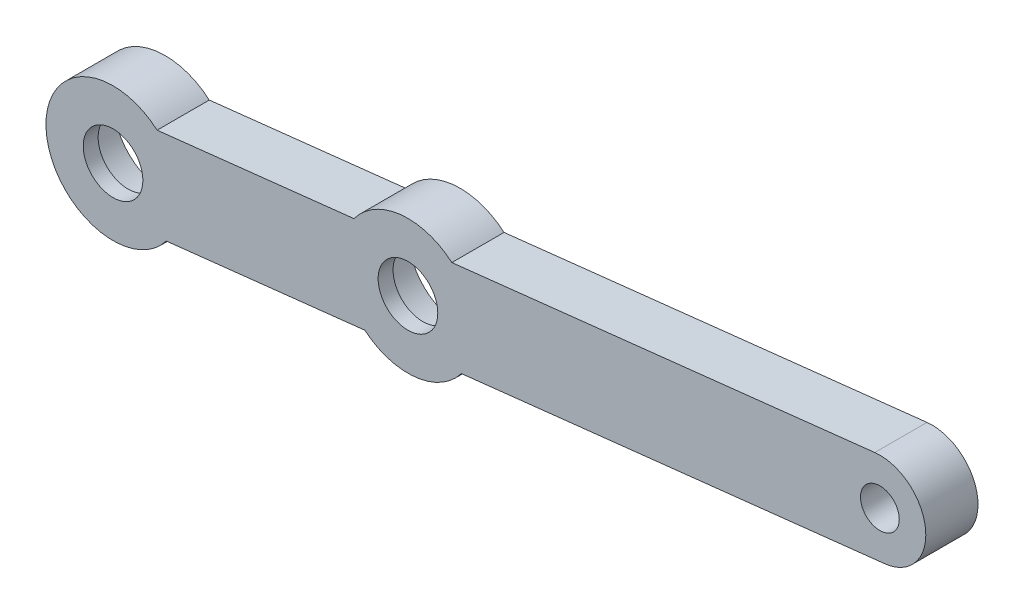
SolidWorks part; units mm, degrees
ref_plane "Front Plane" through (0, 0, 0) normal (0, 0, 1) x (1, 0, 0)
ref_plane "Top Plane" through (0, 0, 0) normal (0, 1, 0) x (1, 0, 0)
ref_plane "Right Plane" through (0, 0, 0) normal (1, 0, 0) x (0, 0, -1)
sketch "Sketch1" plane through (0, 0, 0) normal (0, 0, 1) x (1, 0, 0)
  line L2 (-117.8424, -77.0683) -> (-91.2212, -74.1121)
  line L3 (-92.666, -61.8727) -> (-119.0791, -64.8059)
  line L4 (-22.8116, -54.1154) -> (-79.5428, -60.4154)
  line L6 (-78.2671, -72.6736) -> (-21.4514, -66.3642)
  circle A3 centre (-22.1315, -60.2398) radius 2.6
  circle A4 centre (-85.4292, -67.2234) radius 6.9
  arc A5 (-91.2212, -74.1121) -> (-78.2671, -72.6736) centre (-85.4292, -67.2234) ccw
  arc A6 (-21.4514, -66.3642) -> (-22.8116, -54.1154) centre (-22.1315, -60.2398) ccw
  arc A9 (-79.5428, -60.4154) -> (-92.666, -61.8727) centre (-85.4292, -67.2234) ccw
  circle A10 centre (-124.987, -71.5953) radius 6.9
  arc A11 (-119.0791, -64.8059) -> (-117.8424, -77.0683) centre (-124.987, -71.5953) ccw
extrude "Boss-Extrude1" add sketch "Sketch1" along normal blind 5
sketch "Sketch2" plane through (0, 0, 5) normal (0, 0, 1) x (1, 0, 0)
  line L4 (-22.8116, -54.1154) -> (-79.5428, -60.4154)
  line L5 (-92.666, -61.8727) -> (-119.0791, -64.8059)
  line L6 (-117.8424, -77.0683) -> (-91.2212, -74.1121)
  line L7 (-78.2671, -72.6736) -> (-21.4514, -66.3642)
  line L8 (-22.8116, -54.1154) -> (-79.5428, -60.4154)
  line L9 (-92.666, -61.8727) -> (-119.0791, -64.8059)
  line L10 (-117.8424, -77.0683) -> (-91.2212, -74.1121)
  line L11 (-78.2671, -72.6736) -> (-21.4514, -66.3642)
  circle A0 centre (-22.1315, -60.2398) radius 2.6
  circle A1 centre (-85.4292, -67.2234) radius 4
  circle A2 centre (-124.987, -71.5953) radius 4
  arc A4 (-21.4514, -66.3642) -> (-22.8116, -54.1154) centre (-22.1315, -60.2398) ccw
  arc A5 (-79.5428, -60.4154) -> (-92.666, -61.8727) centre (-85.4292, -67.2234) ccw
  arc A6 (-119.0791, -64.8059) -> (-117.8424, -77.0683) centre (-124.987, -71.5953) ccw
  arc A7 (-91.2212, -74.1121) -> (-78.2671, -72.6736) centre (-85.4292, -67.2234) ccw
  arc A8 (-21.4514, -66.3642) -> (-22.8116, -54.1154) centre (-22.1315, -60.2398) ccw
  arc A9 (-79.5428, -60.4154) -> (-92.666, -61.8727) centre (-85.4292, -67.2234) ccw
  arc A10 (-119.0791, -64.8059) -> (-117.8424, -77.0683) centre (-124.987, -71.5953) ccw
  arc A11 (-91.2212, -74.1121) -> (-78.2671, -72.6736) centre (-85.4292, -67.2234) ccw
  dimension "D2" = 5.2
  dimension "D3" = 8
  dimension "D4" = 8
  dimension "D1" = 0
extrude "Boss-Extrude2" add sketch "Sketch2" along normal blind 2
scale "Scale1" scale about centroid uniform scaling yes scale factor 1.5
